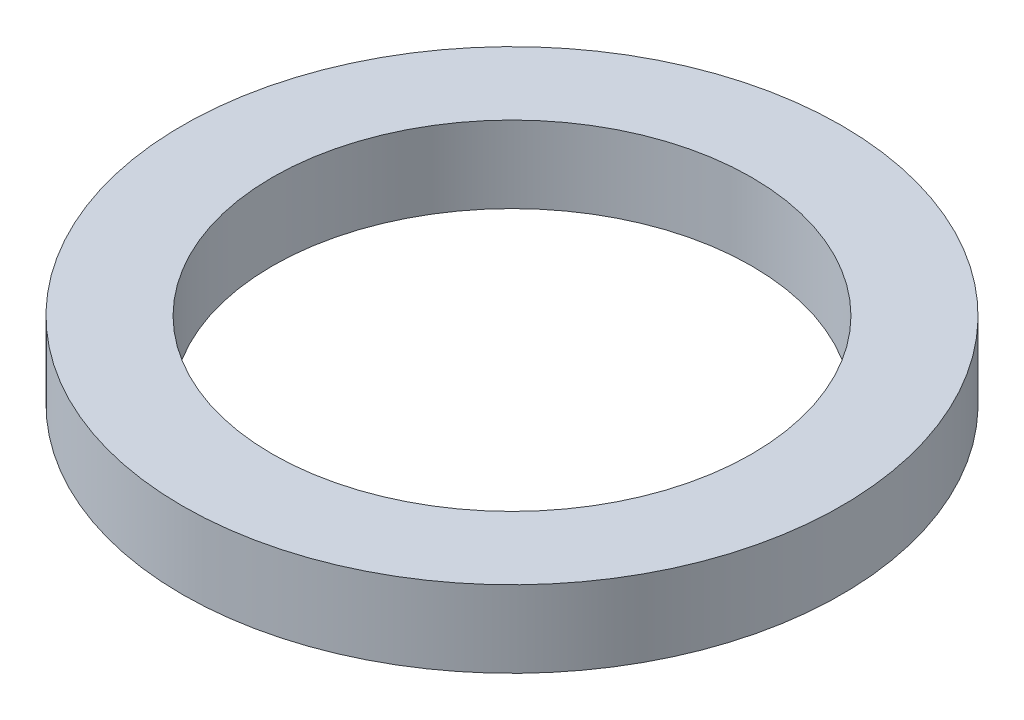
SolidWorks part; units mm, degrees
ref_plane "前视基准面" through (0, 0, 0) normal (0, 0, 1) x (1, 0, 0)
ref_plane "上视基准面" through (0, 0, 0) normal (0, 1, 0) x (1, 0, 0)
ref_plane "右视基准面" through (0, 0, 0) normal (1, 0, 0) x (0, 0, -1)
sketch "草图1" plane through (0, 0, 0) normal (0, 1, 0) x (1, 0, 0)
  circle A0 centre (0, 0) radius 10
  circle A1 centre (0, 0) radius 13.75
extrude "凸台-拉伸1" add sketch "草图1" along normal blind 3.2
